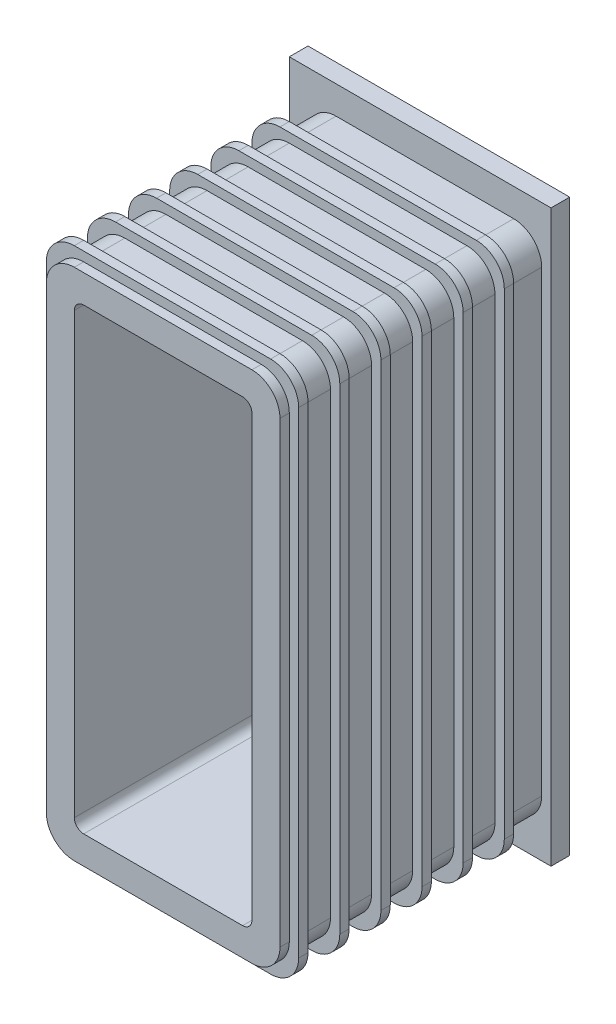
SolidWorks part; units mm, degrees
material "2195 Aluminum"
ref_plane "Front Plane" through (0, 0, 0) normal (0, 0, 1) x (1, 0, 0)
ref_plane "Top Plane" through (0, 0, 0) normal (0, 1, 0) x (1, 0, 0)
ref_plane "Right Plane" through (0, 0, 0) normal (1, 0, 0) x (0, 0, -1)
sketch "Sketch2" plane through (0, 0, 0) normal (0, 0, 1) x (1, 0, 0)
  line L1 (-25, 112.5) -> (25, 112.5)
  line L2 (-25, 112.5) -> (-25, -112.5)
  line L3 (-25, -112.5) -> (25, -112.5)
  line L4 (25, 112.5) -> (25, -112.5)
  line L5 (-15, 102.5) -> (15, 102.5)
  line L6 (-15, 102.5) -> (-15, -102.5)
  line L7 (-15, -102.5) -> (15, -102.5)
  line L8 (15, 102.5) -> (15, -102.5)
  dimension "D1" = 25
  dimension "D2" = 112.5
  dimension "D3" = 50
  dimension "D4" = 225
  dimension "D5" = 10
  dimension "D6" = 10
  dimension "D7" = 10
  dimension "D8" = 10
extrude "Boss-Extrude1" add sketch "Sketch2" against normal blind 25
sketch "Sketch3" plane through (0, 0, 0) normal (0, 0, 1) x (1, 0, 0)
  line L0 (15, 102.5) -> (-15, 102.5) construction
  line L1 (-55, 152.5) -> (85, 152.5)
  line L2 (-55, 152.5) -> (-55, -152.5)
  line L3 (-55, -152.5) -> (85, -152.5)
  line L4 (85, 152.5) -> (85, -152.5)
  line L5 (-15, 102.5) -> (15, 102.5)
  line L6 (-15, 102.5) -> (-15, -102.5)
  line L7 (-15, -102.5) -> (15, -102.5)
  line L8 (15, 102.5) -> (15, -102.5)
  line L9 (-15, 102.5) -> (-15, -102.5) construction
  line L10 (15, -102.5) -> (15, 102.5) construction
  line L11 (-15, -102.5) -> (15, -102.5) construction
  line L12 (25, 112.5) -> (-25, 112.5) construction
  line L13 (25, -112.5) -> (25, 112.5) construction
  line L14 (-25, -112.5) -> (25, -112.5) construction
  line L15 (-25, 112.5) -> (-25, -112.5) construction
  dimension "D1" = 40
  dimension "D2" = 60
  dimension "D3" = 40
  dimension "D4" = 30
extrude "Boss-Extrude2" add sketch "Sketch3" along normal blind 10
sketch "Sketch4" plane through (0, 0, 10) normal (0, 0, 1) x (1, 0, 0)
  line L0 (85, 152.5) -> (-55, 152.5) construction
  line L1 (-30, 137.5) -> (65, 137.5)
  line L2 (-45, 122.5) -> (-45, -122.5)
  line L3 (-30, -137.5) -> (65, -137.5)
  line L4 (80, 122.5) -> (80, -122.5)
  line L5 (85, -152.5) -> (85, 152.5) construction
  line L6 (-55, 152.5) -> (-55, -152.5) construction
  line L7 (-55, -152.5) -> (85, -152.5) construction
  line L9 (-25, 122.5) -> (60, 122.5)
  line L10 (-30, 117.5) -> (-30, -117.5)
  line L11 (-25, -122.5) -> (60, -122.5)
  line L12 (65, 117.5) -> (65, -117.5)
  arc A0 (-45, -122.5) -> (-30, -137.5) centre (-30, -122.5) ccw
  arc A1 (65, -137.5) -> (80, -122.5) centre (65, -122.5) ccw
  arc A2 (65, 137.5) -> (80, 122.5) centre (65, 122.5) cw
  arc A3 (-30, 137.5) -> (-45, 122.5) centre (-30, 122.5) ccw
  arc A4 (-30, -117.5) -> (-25, -122.5) centre (-25, -117.5) ccw
  arc A5 (60, -122.5) -> (65, -117.5) centre (60, -117.5) ccw
  arc A6 (60, 122.5) -> (65, 117.5) centre (60, 117.5) cw
  arc A7 (-25, 122.5) -> (-30, 117.5) centre (-25, 117.5) ccw
  dimension "D5" = 15
  dimension "D6" = 5
  dimension "D1" = 15
  dimension "D2" = 5
  dimension "D3" = 10
  dimension "D4" = 15
extrude "Boss-Extrude3" add sketch "Sketch4" along normal blind 140
sketch "Sketch5" plane through (0, 0, 10) normal (0, 0, 1) x (1, 0, 0)
  line L0 (65, 137.5) -> (-30, 137.5) construction
  line L1 (-35, 142.5) -> (70, 142.5)
  line L2 (-50, 127.5) -> (-50, -127.5)
  line L3 (-35, -142.5) -> (70, -142.5)
  line L4 (85, 127.5) -> (85, -127.5)
  line L5 (-45, 122.5) -> (-45, -122.5) construction
  line L6 (-30, -137.5) -> (65, -137.5) construction
  line L7 (80, -122.5) -> (80, 122.5) construction
  line L8 (80, -122.5) -> (80, 122.5) construction
  line L9 (-30, 137.5) -> (65, 137.5)
  line L10 (-45, 122.5) -> (-45, -122.5)
  line L11 (-30, -137.5) -> (65, -137.5)
  line L12 (80, 122.5) -> (80, -122.5)
  arc A1 (-50, -127.5) -> (-35, -142.5) centre (-35, -127.5) ccw
  arc A2 (70, -142.5) -> (85, -127.5) centre (70, -127.5) ccw
  arc A3 (70, 142.5) -> (85, 127.5) centre (70, 127.5) cw
  arc A4 (-35, 142.5) -> (-50, 127.5) centre (-35, 127.5) ccw
  arc A5 (-30, 137.5) -> (-45, 122.5) centre (-30, 122.5) ccw
  arc A6 (65, 137.5) -> (80, 122.5) centre (65, 122.5) cw
  arc A7 (65, -137.5) -> (80, -122.5) centre (65, -122.5) ccw
  arc A8 (-45, -122.5) -> (-30, -137.5) centre (-30, -122.5) ccw
  dimension "D3" = 5
  dimension "D5" = 15
  dimension "D6" = 15
  dimension "D1" = 5
  dimension "D2" = 5
  dimension "D4" = 5
extrude "Boss-Extrude4" add sketch "Sketch5" along normal blind 5 from offset 20
pattern_linear "LPattern1" count 6 spacing 22 along (0, 0, 1) of "Boss-Extrude4"
